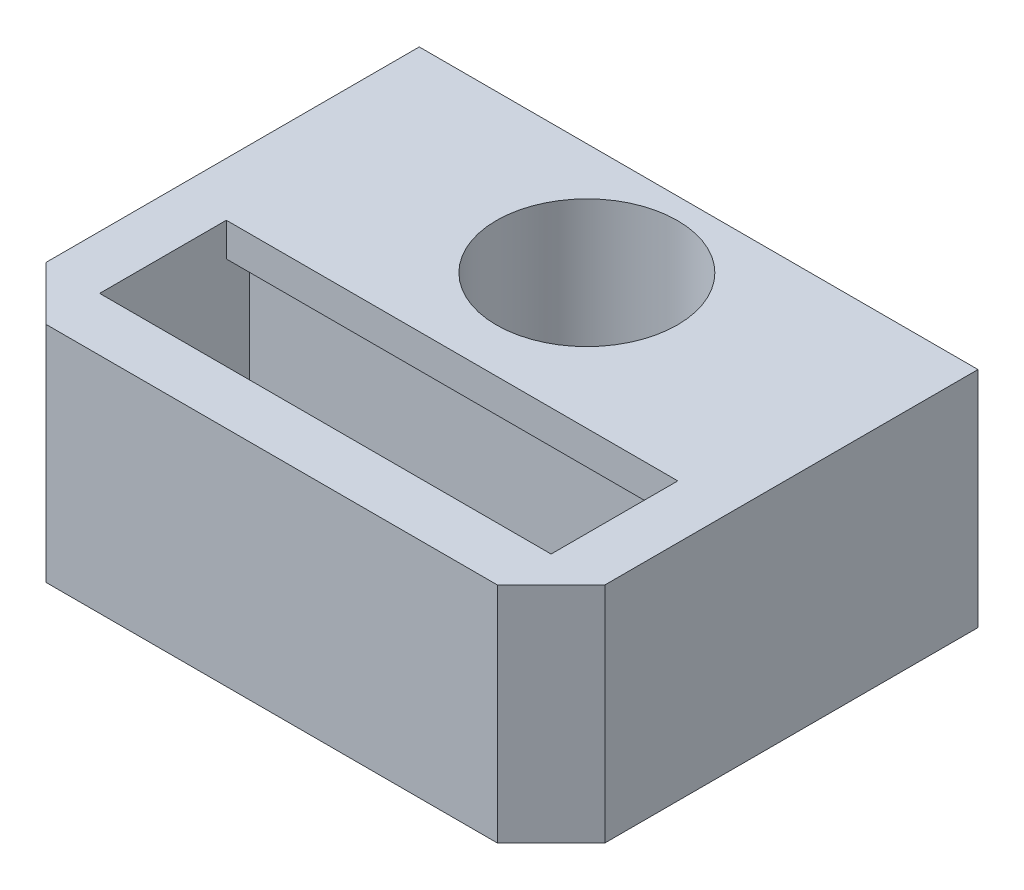
SolidWorks part; units mm, degrees
ref_plane "Plano frontal" through (0, 0, 0) normal (0, 0, 1) x (1, 0, 0)
ref_plane "Plano superior" through (0, 0, 0) normal (0, 1, 0) x (1, 0, 0)
ref_plane "Plano direito" through (0, 0, 0) normal (1, 0, 0) x (0, 0, -1)
sketch "Esboço1" plane through (0, 0, 0) normal (0, 1, 0) x (1, 0, 0)
  line L1 (-12.5, -5) -> (12.5, -5)
  line L2 (-12.5, -5) -> (-12.5, 5)
  line L3 (-12.5, 5) -> (12.5, 5)
  line L4 (12.5, -5) -> (12.5, 5)
  line L5 (-4.6888, -1.8755) -> (4.6888, 1.8755) construction
  line L6 (-3.7603, 1.5041) -> (4.6888, -1.8755) construction
  circle A0 centre (0, 0) radius 4.05
  dimension "D1" = 8.1
  dimension "D3" = 25
  dimension "D4" = 10
extrude "Ressalto-extrusão1" add sketch "Esboço1" along normal blind 10
sketch "Esboço2" plane through (0, 0, 0) normal (0, -1, 0) x (1, 0, 0)
  line L0 (-12.5, 5) -> (-12.5, 11.7)
  line L1 (-10.1, 5) -> (-10.1, 11.7)
  line L2 (0, 0) -> (0, 7.47) construction
  line L3 (10.1, 5) -> (10.1, 11.7)
  line L4 (12.5, 5) -> (12.5, 11.7)
  line L5 (-12.5, 5) -> (-10.1, 5)
  line L6 (10.1, 5) -> (12.5, 5)
  line L7 (-10.1, 11.7) -> (10.1, 11.7)
  line L8 (-12.5, 11.7) -> (-10.1, 14.1)
  line L9 (-10.1, 14.1) -> (10.1, 14.1)
  line L10 (10.1, 14.1) -> (12.5, 11.7)
  dimension "D1" = 6.7
  dimension "D2" = 2.4
extrude "Ressalto-extrusão2" add sketch "Esboço2" against normal blind 10
sketch "Esboço3" plane through (-12.5, 0, 0) normal (-1, 0, 0) x (0, 0, 1)
  line L0 (-5, 10) -> (11.7, 10) construction
  line L1 (4.2788, 10) -> (6.0312, 10)
  line L2 (4.2788, 10) -> (4.2788, 8.5)
  line L3 (4.2788, 8.5) -> (6.0312, 8.5)
  line L4 (6.0312, 10) -> (6.0312, 8.5)
  dimension "D1" = 1.5
extrude "Ressalto-extrusão3" add sketch "Esboço3" against normal through all
